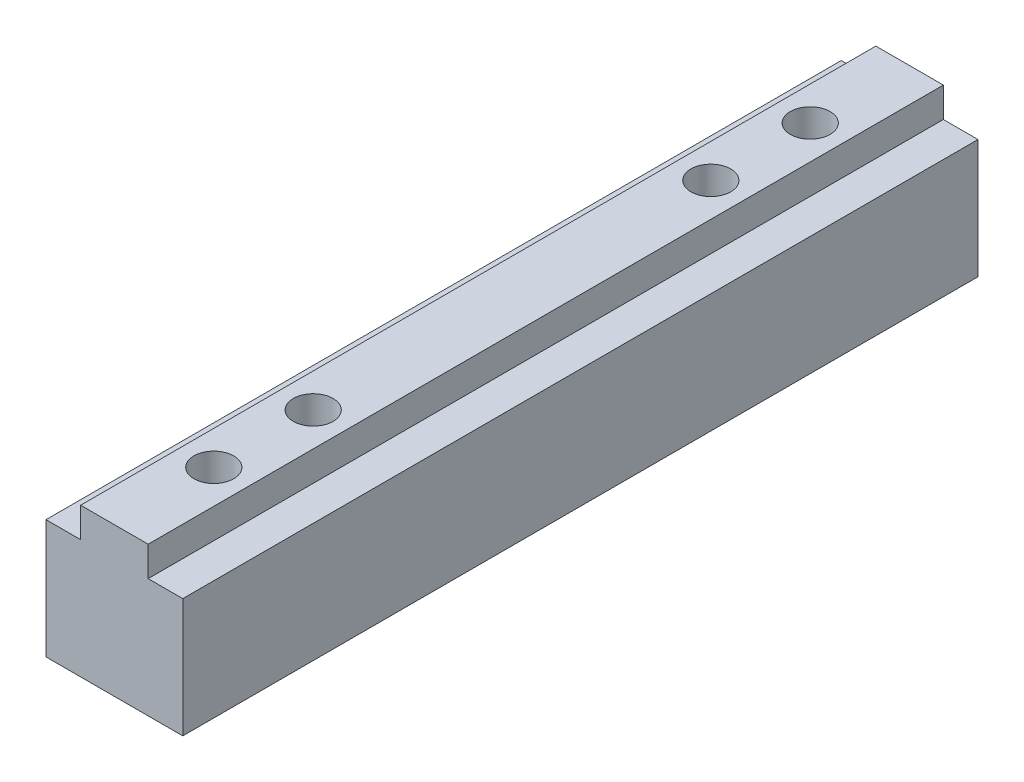
SolidWorks part; units mm, degrees
ref_plane "Front Plane" through (0, 0, 0) normal (0, 0, 1) x (1, 0, 0)
ref_plane "Top Plane" through (0, 0, 0) normal (0, 1, 0) x (1, 0, 0)
ref_plane "Right Plane" through (0, 0, 0) normal (1, 0, 0) x (0, 0, -1)
sketch "Sketch1" plane through (0, 0, 0) normal (0, 1, 0) x (1, 0, 0)
  line L1 (-10.922, -63.5) -> (10.922, -63.5)
  line L2 (-10.922, -63.5) -> (-10.922, 63.5)
  line L3 (-10.922, 63.5) -> (10.922, 63.5)
  line L4 (10.922, -63.5) -> (10.922, 63.5)
  line L5 (-10.922, -63.5) -> (10.922, 63.5) construction
  line L6 (-10.922, 63.5) -> (10.922, -63.5) construction
  line L8 (0, 48.8055) -> (0, 48.6902)
  line L9 (-10.922, 63.5) -> (-10.922, 31.75)
  circle A0 centre (0, -47.625) radius 3.175
  circle A1 centre (0, -31.75) radius 3.175
  circle A2 centre (0, 47.625) radius 3.175
  circle A3 centre (0, 31.75) radius 3.175
  point P0 (0, 0)
  dimension "D3" = 6.35
  dimension "D4" = 6.35
  dimension "D5" = 6.35
  dimension "D6" = 6.35
  dimension "D1" = 127
  dimension "D2" = 21.844
  dimension "D7" = 15.875
  dimension "D8" = 15.875
  dimension "D9" = 15.875
  dimension "D10" = 15.875
extrude "Boss-Extrude1" add sketch "Sketch1" along normal blind 23.749 contours L1 L4 L3 L2 A3 A2 A1 A0
sketch "Sketch3" plane through (0, 23.749, 0) normal (0, 1, 0) x (1, 0, 0)
  line L10 (-10.922, 63.5) -> (10.922, 63.5) construction
  line L11 (-10.922, -63.5) -> (-5.3901, -63.5)
  line L12 (-10.922, -63.5) -> (-10.922, 63.5)
  line L13 (-10.922, 63.5) -> (-5.3901, 63.5)
  line L14 (-5.3901, -63.5) -> (-5.3901, 63.5)
  line L16 (10.922, -63.5) -> (5.3901, -63.5)
  line L17 (10.922, -63.5) -> (10.922, 63.5)
  line L18 (10.922, 63.5) -> (5.3901, 63.5)
  line L19 (5.3901, -63.5) -> (5.3901, 63.5)
extrude "Cut-Extrude2" cut sketch "Sketch3" against normal blind 4.7625
